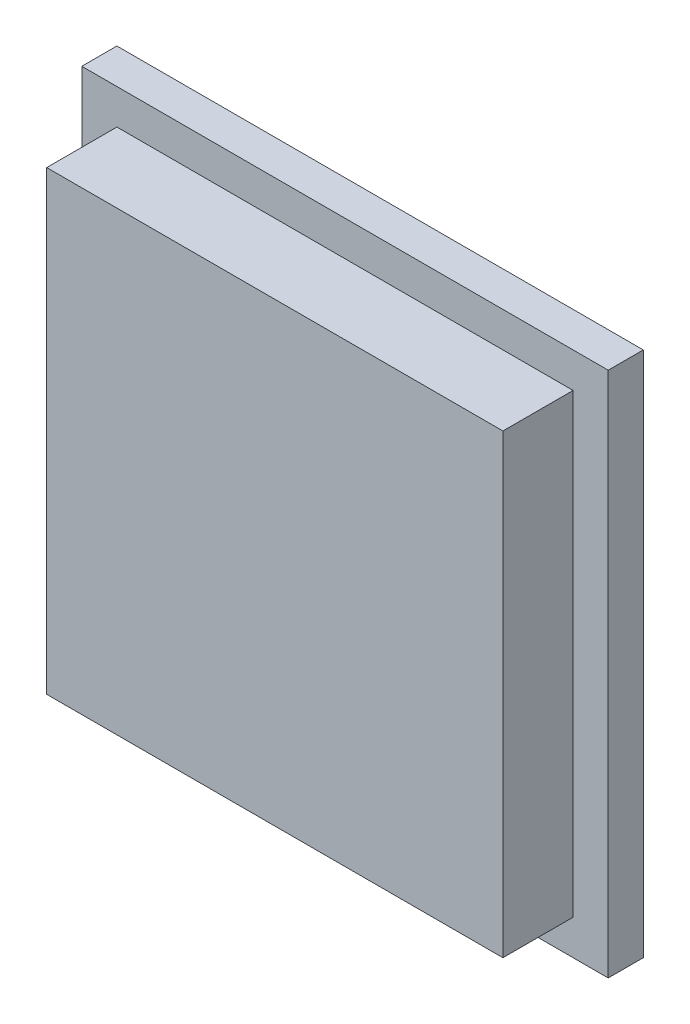
SolidWorks part; units mm, degrees
ref_plane "Front Plane" through (0, 0, 0) normal (0, 0, 1) x (1, 0, 0)
ref_plane "Top Plane" through (0, 0, 0) normal (0, 1, 0) x (1, 0, 0)
ref_plane "Right Plane" through (0, 0, 0) normal (1, 0, 0) x (0, 0, -1)
sketch "Sketch1" plane through (0, 0, 0) normal (0, 0, 1) x (1, 0, 0)
  line L1 (0, 0) -> (150, 0)
  line L2 (0, 0) -> (0, 150)
  line L3 (0, 150) -> (150, 150)
  line L4 (150, 0) -> (150, 150)
  dimension "D1" = 150
  dimension "D2" = 150
extrude "Boss-Extrude1" add sketch "Sketch1" along normal blind 10
sketch "Sketch2" plane through (0, 0, 10) normal (0, 0, 1) x (1, 0, 0)
  line L0 (150, 150) -> (0, 150) construction
  line L1 (10, 140) -> (140, 140)
  line L2 (10, 140) -> (10, 10)
  line L3 (10, 10) -> (140, 10)
  line L4 (140, 140) -> (140, 10)
  line L5 (0, 150) -> (0, 0) construction
  dimension "D1" = 130
  dimension "D2" = 130
  dimension "D3" = 10
  dimension "D4" = 10
extrude "Boss-Extrude2" add sketch "Sketch2" along normal blind 20
